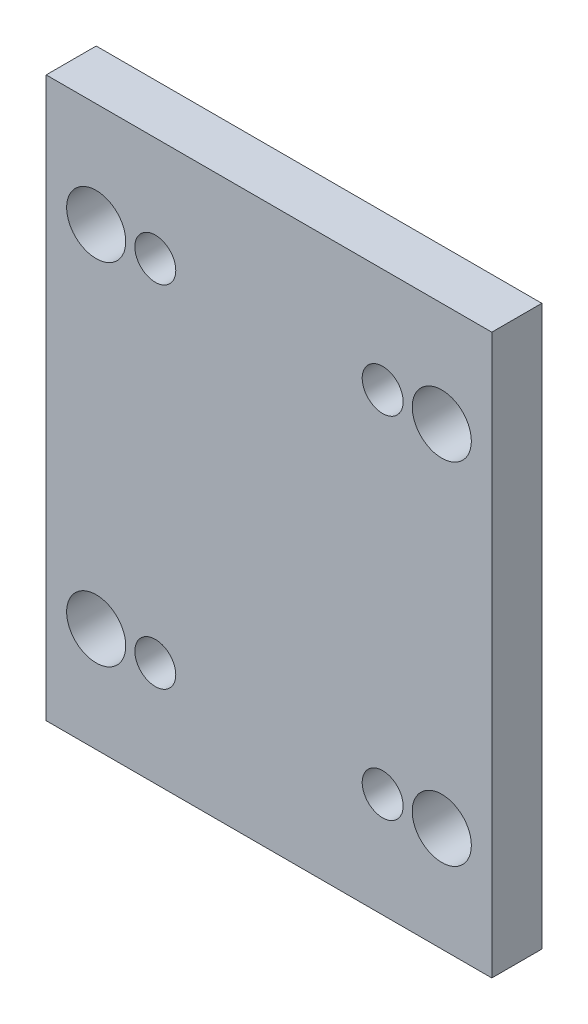
SolidWorks part; units mm, degrees
ref_plane "Спереди" through (0, 0, 0) normal (0, 0, 1) x (1, 0, 0)
ref_plane "Сверху" through (0, 0, 0) normal (0, 1, 0) x (1, 0, 0)
ref_plane "Справа" through (0, 0, 0) normal (1, 0, 0) x (0, 0, -1)
ref_plane "Плоскость4" through (0, 0, 22) normal (0, 0, 1) x (1, 0, 0)
sketch "Эскиз1" plane through (0, 0, 22) normal (0, 0, 1) x (1, 0, 0)
  line L0 (98, 123) -> (-98, 123)
  line L1 (-98, 123) -> (-98, -123)
  line L2 (-98, -123) -> (98, -123)
  line L3 (98, -123) -> (98, 123)
extrude "Бобышка-Вытянуть1" add sketch "Эскиз1" against normal blind 22
hole_wizard "Цековка для  болта с шестигранной головкой M101" positions "Эскиз3" profile "Эскиз2" counterbore size "M10" standard "Ansi Metric"
sketch "Эскиз3" plane through (0, 0, 22) normal (0, 0, 1) x (1, 0, 0)
  point P0 (50, 77)
  point P1 (50, -77)
  point P2 (-50, 77)
  point P3 (-50, -77)
sketch "Эскиз2" plane through (50, 77, 22) normal (1, 0, 0) x (0, -1, 0)
  line L0 (0, 0) -> (0, 22)
  line L1 (0, 22) -> (5.5, 22)
  line L3 (5.5, 22) -> (5.5, 13)
  line L4 (5.5, 13) -> (9, 13)
  line L5 (9, 13) -> (9, 0)
  line L7 (9, 0) -> (0, 0)
  line L11 (0, -6.35) -> (0, 107.95) construction
  dimension "Диаметр сквозного отверстия" = 11
  dimension "Глубина сквозного отверстия" = 22
  dimension "Диаметр цековки" = 18
  dimension "Глубина цековки" = 13
hole_wizard "Отверстие с зазором M221" positions "Эскиз5" profile "Эскиз4" hole size "M22" standard "Ansi Metric"
sketch "Эскиз5" plane through (0, 0, 22) normal (0, 0, 1) x (1, 0, 0)
  point P0 (76, 77)
  point P1 (76, -77)
  point P2 (-76, -77)
  point P3 (-76, 77)
sketch "Эскиз4" plane through (76, 77, 22) normal (1, 0, 0) x (0, -1, 0)
  line L0 (0, 0) -> (0, 22)
  line L1 (0, 22) -> (13, 22)
  line L2 (13, 22) -> (13, 0)
  line L5 (13, 0) -> (0, 0)
  line L11 (0, -6.35) -> (0, 107.95) construction
  dimension "Диаметр сквозного отверстия" = 26
  dimension "Глубина сквозного отверстия" = 22
